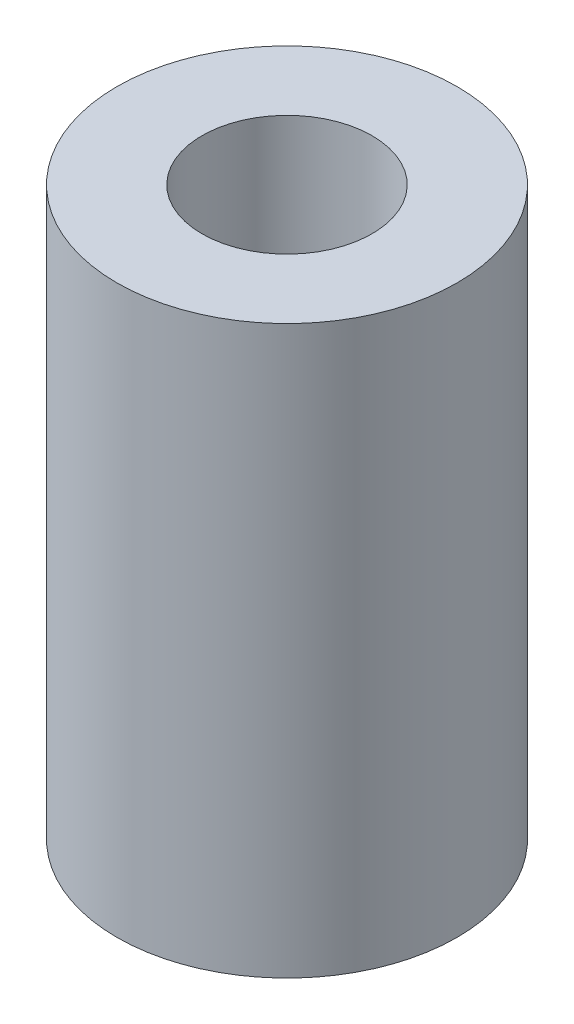
SolidWorks part; units mm, degrees
ref_plane "Front Plane" through (0, 0, 0) normal (0, 0, 1) x (1, 0, 0)
ref_plane "Top Plane" through (0, 0, 0) normal (0, 1, 0) x (1, 0, 0)
ref_plane "Right Plane" through (0, 0, 0) normal (1, 0, 0) x (0, 0, -1)
sketch "Sketch1" plane through (0, 0, 0) normal (0, 1, 0) x (1, 0, 0)
  circle A0 centre (0, 0) radius 3
  circle A1 centre (0, 0) radius 1.5
  dimension "D1" = 1.5
  dimension "D2" = 3
extrude "Boss-Extrude1" add sketch "Sketch1" along normal blind 10
